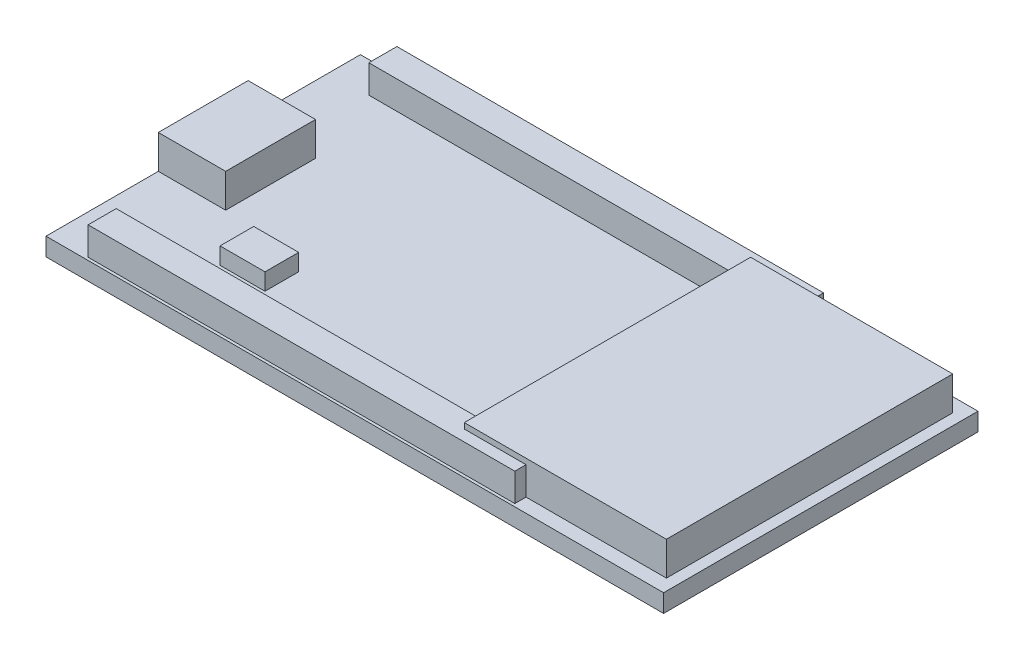
SolidWorks part; units mm, degrees
ref_plane "Front Plane" through (0, 0, 0) normal (0, 0, 1) x (1, 0, 0)
ref_plane "Top Plane" through (0, 0, 0) normal (0, 1, 0) x (1, 0, 0)
ref_plane "Right Plane" through (0, 0, 0) normal (1, 0, 0) x (0, 0, -1)
other "Configuration Table"
sketch "Sketch1" plane through (0, 0, 0) normal (0, 1, 0) x (1, 0, 0)
  line L1 (-27.5, -14) -> (27.5, -14)
  line L2 (-27.5, -14) -> (-27.5, 14)
  line L3 (-27.5, 14) -> (27.5, 14)
  line L4 (27.5, -14) -> (27.5, 14)
  line L5 (-27.5, -14) -> (27.5, 14) construction
  line L6 (-27.5, 14) -> (27.5, -14) construction
extrude "PCB" add sketch "Sketch1" along normal blind 1.6
sketch "Sketch2" plane through (0, 0, 0) normal (0, 1, 0) x (1, 0, 0)
  line L1 (8.5, -12.75) -> (26.5, -12.75)
  line L2 (8.5, -12.75) -> (8.5, 12.75)
  line L3 (8.5, 12.75) -> (26.5, 12.75)
  line L4 (26.5, -12.75) -> (26.5, 12.75)
  line L5 (8.5, -12.75) -> (26.5, 12.75) construction
  line L6 (8.5, 12.75) -> (26.5, -12.75) construction
extrude "WROOM_Shield" add sketch "Sketch2" along normal blind 3 from offset 1.6
sketch "Sketch3" plane through (0, 0, 0) normal (0, 1, 0) x (1, 0, 0)
  line L1 (-27.5, -4) -> (-21.5, -4)
  line L2 (-27.5, -4) -> (-27.5, 4)
  line L3 (-27.5, 4) -> (-21.5, 4)
  line L4 (-21.5, -4) -> (-21.5, 4)
  line L5 (-27.5, -4) -> (-21.5, 4) construction
  line L6 (-27.5, 4) -> (-21.5, -4) construction
extrude "Micro_USB" add sketch "Sketch3" along normal blind 3 from offset 1.6
sketch "Sketch4" plane through (0, 0, 0) normal (0, 1, 0) x (1, 0, 0)
  line L1 (-24, -13.75) -> (14, -13.75)
  line L2 (-24, -13.75) -> (-24, -11.25)
  line L3 (-24, -11.25) -> (14, -11.25)
  line L4 (14, -13.75) -> (14, -11.25)
  line L5 (-24, -13.75) -> (14, -11.25) construction
  line L6 (-24, -11.25) -> (14, -13.75) construction
extrude "Header_1" add sketch "Sketch4" along normal blind 2.5 from offset 1.6
sketch "Sketch5" plane through (0, 0, 0) normal (0, 1, 0) x (1, 0, 0)
  line L1 (-24, 11.25) -> (14, 11.25)
  line L2 (-24, 11.25) -> (-24, 13.75)
  line L3 (-24, 13.75) -> (14, 13.75)
  line L4 (14, 11.25) -> (14, 13.75)
  line L5 (-24, 11.25) -> (14, 13.75) construction
  line L6 (-24, 13.75) -> (14, 11.25) construction
extrude "Header_2" add sketch "Sketch5" along normal blind 2.5 from offset 1.6
sketch "Sketch6" plane through (0, 0, 0) normal (0, 1, 0) x (1, 0, 0)
  line L1 (-17.5, -8.5) -> (-13.5, -8.5)
  line L2 (-17.5, -8.5) -> (-17.5, -5.5)
  line L3 (-17.5, -5.5) -> (-13.5, -5.5)
  line L4 (-13.5, -8.5) -> (-13.5, -5.5)
  line L5 (-17.5, -8.5) -> (-13.5, -5.5) construction
  line L6 (-17.5, -5.5) -> (-13.5, -8.5) construction
extrude "Button_EN" add sketch "Sketch6" along normal blind 1.5 from offset 1.6
equation "\"esp_L\"= 55.0   'ASSUMPTION: ESP32 DevKit V1 board L (PDF fallback)"
equation "\"esp_W\"= 28.0   'ASSUMPTION: ESP32 DevKit V1 board W (PDF fallback)"
equation "\"pcb_t\"= 1.6   'ASSUMPTION: PCB thickness (standard)"
equation "\"D1@PCB\" = \"pcb_t\""
